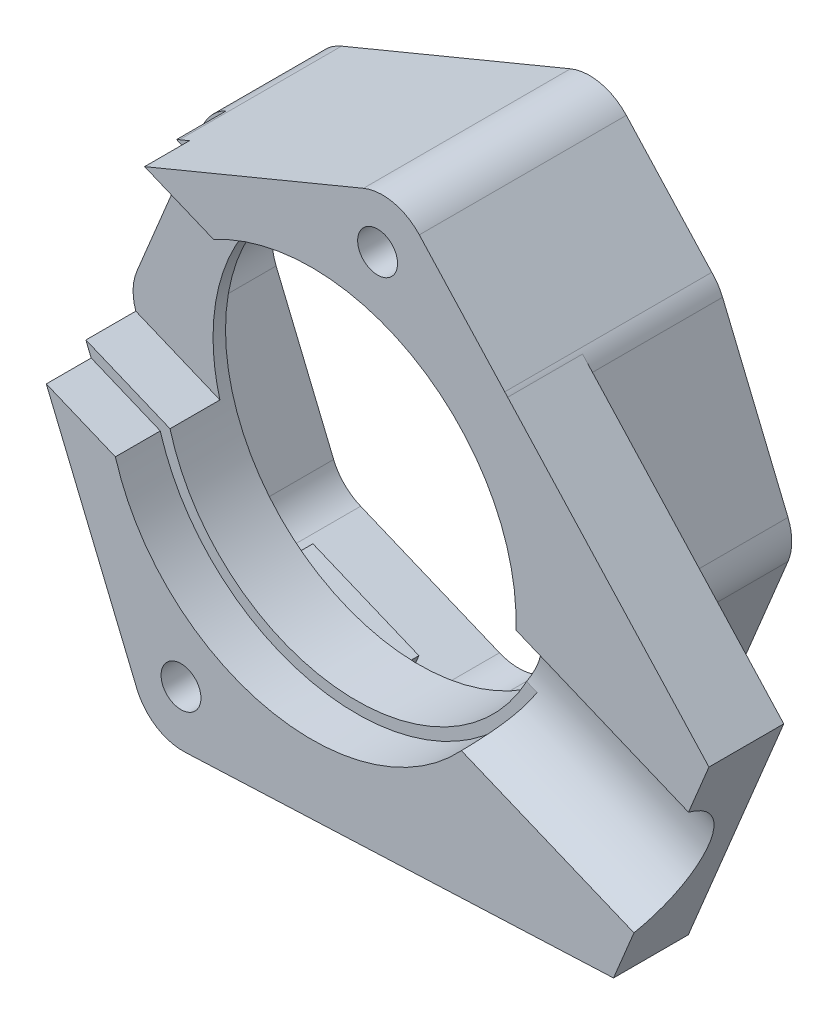
SolidWorks part; units mm, degrees
other "Markup1"
sketch "Sketch20" plane through (-10.9556, -11.1787, -0.014) normal (-0.7276, -0.6044, -0.3245) x (0.4643, -0.7821, 0.4157)
ref_plane "Front Plane" through (0, 0, 0) normal (0, 0, 1) x (1, 0, 0)
ref_plane "Top Plane" through (0, 0, 0) normal (0, 1, 0) x (1, 0, 0)
ref_plane "Right Plane" through (0, 0, 0) normal (1, 0, 0) x (0, 0, -1)
sketch "Sketch1" plane through (0, 0, 0) normal (0, 0, 1) x (1, 0, 0)
  line L0 (9.8215, 0) -> (-9.8215, 0) construction
  line L1 (0, 9.8215) -> (0, -9.8215) construction
  line L2 (-6.9448, -6.9448) -> (6.9448, 6.9448) construction
  line L3 (6.9448, -6.9448) -> (-6.9448, 6.9448) construction
  line L4 (9.8215, 0) -> (6.9448, -6.9448) construction
  line L5 (6.9448, -6.9448) -> (0, -9.8215) construction
  line L6 (0, -9.8215) -> (-6.9448, -6.9448) construction
  line L7 (-6.9448, -6.9448) -> (-9.8215, 0) construction
  line L8 (-9.8215, 0) -> (-6.9448, 6.9448) construction
  line L9 (-6.9448, 6.9448) -> (0, 9.8215) construction
  line L10 (0, 9.8215) -> (6.9448, 6.9448) construction
  line L11 (6.9448, 6.9448) -> (9.8215, 0) construction
  line L12 (8.8215, 0) -> (6.2377, -6.2377) construction
  line L13 (6.2377, -6.2377) -> (0, -8.8215) construction
  line L14 (0, -8.8215) -> (-6.2377, -6.2377) construction
  line L15 (-6.2377, -6.2377) -> (-8.8215, 0) construction
  line L16 (-8.8215, 0) -> (-6.2377, 6.2377) construction
  line L17 (-6.2377, 6.2377) -> (0, 8.8215) construction
  line L18 (0, 8.8215) -> (6.2377, 6.2377) construction
  line L19 (6.2377, 6.2377) -> (8.8215, 0) construction
  line L20 (-7.0979, 7.0979) -> (0, 10.038)
  line L21 (0, 10.038) -> (7.0979, 7.0979)
  line L22 (7.0979, 7.0979) -> (10.038, 0)
  line L23 (10.038, 0) -> (7.0979, -7.0979)
  line L24 (7.0979, -7.0979) -> (0, -10.038)
  line L25 (0, -10.038) -> (-7.0979, -7.0979)
  line L26 (-7.0979, -7.0979) -> (-10.038, 0)
  line L27 (-10.038, 0) -> (-7.0979, 7.0979)
  line L28 (-8.605, 0) -> (-6.0847, 6.0847)
  line L29 (-6.0847, 6.0847) -> (0, 8.605)
  line L30 (0, 8.605) -> (6.0847, 6.0847)
  line L31 (6.0847, 6.0847) -> (8.605, 0)
  line L32 (8.605, 0) -> (6.0847, -6.0847)
  line L33 (6.0847, -6.0847) -> (0, -8.605)
  line L34 (0, -8.605) -> (-6.0847, -6.0847)
  line L35 (-6.0847, -6.0847) -> (-8.605, 0)
  line L36 (-11.1204, 0) -> (-7.8633, 7.8633)
  line L37 (-7.8633, 7.8633) -> (0, 11.1204)
  line L38 (0, 11.1204) -> (7.8633, 7.8633)
  line L39 (7.8633, 7.8633) -> (11.1204, 0)
  line L40 (11.1204, 0) -> (7.8633, -7.8633)
  line L41 (7.8633, -7.8633) -> (0, -11.1204)
  line L42 (0, -11.1204) -> (-7.8633, -7.8633)
  line L43 (-7.8633, -7.8633) -> (-11.1204, 0)
  circle A0 centre (0, 0) radius 8.8215 construction
  circle A1 centre (0, 0) radius 9.8215 construction
  dimension "D1" = 1
  dimension "D2" = 8.15
  dimension "D3" = 45
  dimension "D4" = 45
  dimension "D5" = 0.2
  dimension "D6" = 0.2
  dimension "D7" = 1
extrude "Boss-Extrude1" add sketch "Sketch1" along normal blind 6 contours L36 L37 L38 L39 L40 L41 L42 L43 | L30 L31 L32 L33 L34 L35 L28 L29 | L21 L22 L23 L24 L25 L26 L27 L20
sketch "Sketch3" plane through (0, 0, 0) normal (0, 0, -1) x (-1, 0, 0)
  line L28 (6.0847, 6.0847) -> (0, 8.605)
  line L29 (0, 8.605) -> (-6.0847, 6.0847)
  line L30 (-6.0847, 6.0847) -> (-8.605, 0)
  line L31 (-8.605, 0) -> (-6.0847, -6.0847)
  line L32 (-6.0847, -6.0847) -> (0, -8.605)
  line L33 (0, -8.605) -> (6.0847, -6.0847)
  line L34 (6.0847, -6.0847) -> (8.605, 0)
  line L35 (8.605, 0) -> (6.0847, 6.0847)
  line L36 (6.0847, 6.0847) -> (0, 8.605)
  line L37 (0, 8.605) -> (-6.0847, 6.0847)
  line L38 (-6.0847, 6.0847) -> (-8.605, 0)
  line L39 (-8.605, 0) -> (-6.0847, -6.0847)
  line L40 (-6.0847, -6.0847) -> (0, -8.605)
  line L41 (0, -8.605) -> (6.0847, -6.0847)
  line L42 (6.0847, -6.0847) -> (8.605, 0)
  line L43 (8.605, 0) -> (6.0847, 6.0847)
  dimension "D5" = 0
extrude "Cut-Extrude1" cut sketch "Sketch3" against normal blind 4
sketch "Sketch4" plane through (0, 0, 6) normal (0, 0, 1) x (1, 0, 0)
  line L16 (-11.1204, 0) -> (-7.8633, -7.8633)
  line L17 (-7.8633, -7.8633) -> (0, -11.1204)
  line L18 (0, -11.1204) -> (7.8633, -7.8633)
  line L19 (7.8633, -7.8633) -> (11.1204, 0)
  line L20 (11.1204, 0) -> (7.8633, 7.8633)
  line L21 (7.8633, 7.8633) -> (0, 11.1204)
  line L22 (0, 11.1204) -> (-7.8633, 7.8633)
  line L23 (-7.8633, 7.8633) -> (-11.1204, 0)
  line L24 (-11.1204, 0) -> (-7.8633, -7.8633)
  line L25 (-7.8633, -7.8633) -> (0, -11.1204)
  line L26 (0, -11.1204) -> (7.8633, -7.8633)
  line L27 (7.8633, -7.8633) -> (11.1204, 0)
  line L28 (11.1204, 0) -> (7.8633, 7.8633)
  line L29 (7.8633, 7.8633) -> (0, 11.1204)
  line L30 (0, 11.1204) -> (-7.8633, 7.8633)
  line L31 (-7.8633, 7.8633) -> (-11.1204, 0)
  dimension "D1" = 0
extrude "Boss-Extrude2" add sketch "Sketch4" against normal blind 2 and the other way blind 0.5
sketch "Sketch5" plane through (0, 0, 0) normal (0, 0, -1) x (-1, 0, 0)
  line L0 (-7.6911, 5.6659) -> (-9.4514, 1.4161)
  line L1 (-7.0979, 7.0979) -> (-10.038, 0) construction
  line L2 (-9.4514, 1.4161) -> (-8.4352, 0.9951)
  line L3 (-8.4352, 0.9951) -> (-6.6748, 5.245)
  line L4 (-6.6748, 5.245) -> (-7.6911, 5.6659)
  line L5 (1.4161, -9.4514) -> (5.6659, -7.6911)
  line L6 (0, -10.038) -> (7.0979, -7.0979) construction
  line L7 (5.6659, -7.6911) -> (5.245, -6.6748)
  line L8 (5.245, -6.6748) -> (0.9951, -8.4352)
  line L9 (0.9951, -8.4352) -> (1.4161, -9.4514)
  point P10 (-8.9433, 1.2056)
  dimension "D1" = 4.6
  dimension "D2" = 4.6
  dimension "D3" = 1.55
  dimension "D4" = 1.55
extrude "Boss-Extrude3" add sketch "Sketch5" against normal up to next from offset 3 offset against normal yes
sketch "Sketch6" plane through (0, 0, 4) normal (0, 0, -1) x (-1, 0, 0)
  circle A0 centre (0, 0) radius 7.75
extrude "Cut-Extrude2" cut sketch "Sketch6" against normal through all
fillet "Fillet1" radius 2 16 edges at (7.0979, -7.0979, 2) (0, -10.038, 2) (-7.0979, -7.0979, 2) (-10.038, 0, 2) (-7.0979, 7.0979, 2) (7.0979, 7.0979, 2) (0, 10.038, 2) (0, 11.1204, 3.25) (7.8633, 7.8633, 3.25) (11.1204, 0, 3.25) (7.8633, -7.8633, 3.25) (0, -11.1204, 3.25) (-7.8633, -7.8633, 3.25) (-11.1204, 0, 3.25) (-7.8633, 7.8633, 3.25) (10.038, 0, 2)
sketch "Sketch7" plane through (0, 0, 6.5) normal (0, 0, 1) x (1, 0, 0)
  line L0 (-3.912, 6.9783) -> (-7.2819, 8.3741)
  line L1 (-9.5916, 7.4174) -> (-12.0272, 1.5374)
  line L2 (-11.0705, -0.7723) -> (-7.7006, -2.1682)
  line L3 (-7.2819, 8.3741) -> (-9.5916, 7.4174)
  line L4 (-11.0705, -0.7723) -> (-12.0272, 1.5374)
  arc A0 (-7.7006, -2.1682) -> (-3.912, 6.9783) centre (0, 0) ccw
  circle A2 centre (-7.5621, 5.7842) radius 2
  circle A3 centre (-9.4373, 1.2572) radius 2
  circle A4 centre (0, 0) radius 5
  dimension "D1" = 9.9
  dimension "D3" = 16
  dimension "D9" = 4
  dimension "D10" = 4
  dimension "D2" = 4.95
  dimension "D4" = 11.7
  dimension "D5" = 45
  dimension "D6" = 45
  dimension "D7" = 2.5
  dimension "D8" = 2.5
  dimension "D11" = 2.5
  dimension "D12" = 2.5
  dimension "D13" = 2.5
  dimension "D14" = 2.5
sketch "Sketch9" plane through (0, 0, 6.5) normal (0, 0, 1) x (1, 0, 0)
  line L16 (7.0979, 8.1803) -> (0.7654, 10.8033)
  line L17 (-0.7654, 10.8033) -> (-7.0979, 8.1803)
  line L18 (-8.1803, 7.0979) -> (-10.8033, 0.7654)
  line L19 (-10.8033, -0.7654) -> (-8.1803, -7.0979)
  line L20 (-7.0979, -8.1803) -> (-0.7654, -10.8033)
  line L21 (0.7654, -10.8033) -> (7.0979, -8.1803)
  line L22 (8.1803, -7.0979) -> (10.8033, -0.7654)
  line L23 (10.8033, 0.7654) -> (8.1803, 7.0979)
  line L24 (7.0979, 8.1803) -> (0.7654, 10.8033)
  line L25 (-0.7654, 10.8033) -> (-7.0979, 8.1803)
  line L26 (-8.1803, 7.0979) -> (-10.8033, 0.7654)
  line L27 (-10.8033, -0.7654) -> (-8.1803, -7.0979)
  line L28 (-7.0979, -8.1803) -> (-0.7654, -10.8033)
  line L29 (0.7654, -10.8033) -> (7.0979, -8.1803)
  line L30 (8.1803, -7.0979) -> (10.8033, -0.7654)
  line L31 (10.8033, 0.7654) -> (8.1803, 7.0979)
  line L125 (-3.8355, 7.163) -> (-7.2054, 8.5589)
  line L126 (-3.9245, 7.1999) -> (-6.6947, 8.3473)
  line L128 (-11.147, -0.9571) -> (-7.7771, -2.3529)
  line L129 (-10.6363, -1.1686) -> (-7.8661, -2.3161)
  arc A8 (-7.8661, -2.3161) -> (-3.9245, 7.1999) centre (0, 0) ccw
  arc A16 (0.7654, 10.8033) -> (-0.7654, 10.8033) centre (0, 8.9556) ccw
  arc A17 (-7.0979, 8.1803) -> (-8.1803, 7.0979) centre (-6.3326, 6.3326) ccw
  arc A18 (-10.8033, 0.7654) -> (-10.8033, -0.7654) centre (-8.9556, 0) ccw
  arc A19 (-8.1803, -7.0979) -> (-7.0979, -8.1803) centre (-6.3326, -6.3326) ccw
  arc A20 (-0.7654, -10.8033) -> (0.7654, -10.8033) centre (0, -8.9556) ccw
  arc A21 (7.0979, -8.1803) -> (8.1803, -7.0979) centre (6.3326, -6.3326) ccw
  arc A22 (10.8033, -0.7654) -> (10.8033, 0.7654) centre (8.9556, 0) ccw
  arc A23 (8.1803, 7.0979) -> (7.0979, 8.1803) centre (6.3326, 6.3326) ccw
  arc A24 (0.7654, 10.8033) -> (-0.7654, 10.8033) centre (0, 8.9556) ccw
  arc A25 (-7.0979, 8.1803) -> (-8.1803, 7.0979) centre (-6.3326, 6.3326) ccw
  arc A26 (-10.8033, 0.7654) -> (-10.8033, -0.7654) centre (-8.9556, 0) ccw
  arc A27 (-8.1803, -7.0979) -> (-7.0979, -8.1803) centre (-6.3326, -6.3326) ccw
  arc A28 (-0.7654, -10.8033) -> (0.7654, -10.8033) centre (0, -8.9556) ccw
  arc A29 (7.0979, -8.1803) -> (8.1803, -7.0979) centre (6.3326, -6.3326) ccw
  arc A30 (10.8033, -0.7654) -> (10.8033, 0.7654) centre (8.9556, 0) ccw
  arc A31 (8.1803, 7.0979) -> (7.0979, 8.1803) centre (6.3326, 6.3326) ccw
  line M21 (7.0979, 8.1803) -> (0.7654, 10.8033)
  arc M22 (0.7654, 10.8033) -> (-0.7654, 10.8033) centre (0, 8.9556) ccw
  line M23 (-0.7654, 10.8033) -> (-7.0979, 8.1803)
  arc M28 (-8.1803, -7.0979) -> (-7.0979, -8.1803) centre (-6.3326, -6.3326) ccw
  line M29 (-7.0979, -8.1803) -> (-0.7654, -10.8033)
  arc M30 (-0.7654, -10.8033) -> (0.7654, -10.8033) centre (0, -8.9556) ccw
  line M31 (0.7654, -10.8033) -> (7.0979, -8.1803)
  arc M32 (7.0979, -8.1803) -> (8.1803, -7.0979) centre (6.3326, -6.3326) ccw
  line M33 (8.1803, -7.0979) -> (10.8033, -0.7654)
  arc M34 (10.8033, -0.7654) -> (10.8033, 0.7654) centre (8.9556, 0) ccw
  line M35 (10.8033, 0.7654) -> (8.1803, 7.0979)
  arc M36 (8.1803, 7.0979) -> (7.0979, 8.1803) centre (6.3326, 6.3326) ccw
  dimension "D2" = 0.2
  dimension "D1" = 0
  dimension "D3" = 0.2
extrude "Boss-Extrude4" add sketch "Sketch9" along normal blind 1.8 contours A8 L129 L27 L126 M28 M29 M30 M31 M32 M33 M34 M35 M36 M21 M22 M23
sketch "Sketch10" plane through (0, 0, 6.5) normal (0, 0, 1) x (1, 0, 0)
  line L0 (-8.8488, 8.8067) -> (-3.1519, 6.4469)
  line L2 (-3.1519, 6.4469) -> (-6.7874, -2.3299)
  line L3 (-6.7874, -2.3299) -> (-12.4843, 0.0298)
  line L4 (-12.4843, 0.0298) -> (-8.8488, 8.8067)
  line L8 (-3.912, 6.9783) -> (-7.2819, 8.3741) construction
  line L9 (-11.0705, -0.7723) -> (-7.7006, -2.1682) construction
  dimension "D1" = 0.2
  dimension "D2" = 0.2
extrude "Cut-Extrude3" cut sketch "Sketch10" against normal blind 2 contours L4 L0 L2 L3
sketch "Sketch12" plane through (0, 0, 8.3) normal (0, 0, 1) x (1, 0, 0)
  line L3 (0, -10.9556) -> (12.1073, -10.427)
  line L4 (12.1073, -10.427) -> (15.9341, -1.1882)
  line L5 (15.9341, -1.1882) -> (7.7468, 7.7468)
  line L19 (0, -10.9556) -> (0.4588, -9.8479)
  line L20 (7.288, 6.6391) -> (7.7468, 7.7468)
  line L22 (9.8795, 0.3827) -> (7.2564, 6.7152)
  line L23 (7.2564, -6.7152) -> (9.8795, -0.3827)
  line L24 (0.3827, -9.8795) -> (6.7152, -7.2564)
  line L25 (9.8795, 0.3827) -> (7.288, 6.6391)
  line L26 (7.2564, -6.7152) -> (9.8795, -0.3827)
  line L27 (0.4588, -9.8479) -> (6.7152, -7.2564)
  arc A0 (-0.7654, -10.8033) -> (0.7654, -10.8033) centre (0, -8.9556) ccw construction
  arc A1 (8.1803, 7.0979) -> (7.0979, 8.1803) centre (6.3326, 6.3326) ccw construction
  arc A24 (7.2564, 6.7152) -> (6.7152, 7.2564) centre (6.3326, 6.3326) ccw
  arc A25 (9.8795, -0.3827) -> (9.8795, 0.3827) centre (8.9556, 0) ccw
  arc A26 (6.7152, -7.2564) -> (7.2564, -6.7152) centre (6.3326, -6.3326) ccw
  arc A27 (-0.3827, -9.8795) -> (0.3827, -9.8795) centre (0, -8.9556) ccw
  arc A29 (9.8795, -0.3827) -> (9.8795, 0.3827) centre (8.9556, 0) ccw
  arc A30 (6.7152, -7.2564) -> (7.2564, -6.7152) centre (6.3326, -6.3326) ccw
  dimension "D2" = 10
  dimension "D3" = 115
  dimension "D4" = 115
  dimension "D1" = 1
extrude "Boss-Extrude5" add sketch "Sketch12" against normal blind 3
sketch "Sketch11" plane through (14.0207, -5.8076, 0) normal (0.9239, -0.3827, 0) x (0, 0, -1)
  line L0 (-8.3, -3.4272) -> (-8.3, 3.4272) construction
  circle A0 centre (-9.5, 0) radius 3.1
  dimension "D1" = 1.2
extrude "Cut-Extrude4" cut sketch "Sketch11" against normal up to surface (8.0729 mm away) contours A0
sketch "Sketch13" plane through (0, 0, 8.3) normal (0, 0, 1) x (1, 0, 0)
  line L0 (-8.1803, -7.0979) -> (-7.0014, -9.9441)
  line L2 (0.1743, -10.948) -> (-5.0664, -11.1768)
  line L4 (-8.1803, -7.0979) -> (0.1743, -10.948)
  line L5 (7.8646, 7.6181) -> (4.3207, 11.4857)
  line L7 (-0.7654, 10.8033) -> (2.0808, 11.9823)
  line L9 (-0.7654, 10.8033) -> (7.8646, 7.6181)
  arc A0 (-7.0014, -9.9441) -> (-5.0664, -11.1768) centre (-5.1536, -9.1787) ccw
  arc A1 (4.3207, 11.4857) -> (2.0808, 11.9823) centre (2.8461, 10.1345) ccw
  dimension "D1" = 2
extrude "Boss-Extrude6" add sketch "Sketch13" against normal up to surface (8.3 mm away) up to face at (0, 0, 0)
sketch "Sketch14" plane through (0, 0, 8.3) normal (0, 0, 1) x (1, 0, 0)
  line L0 (-0.0089, -0.0215) -> (7.7271, 18.6549) construction
  line L1 (-5.2351, -8.9802) -> (-1.2934, 0.5358) construction
  line L2 (0.0034, -0.0014) -> (-15.1897, 6.2918) construction
  line L4 (-1.2934, 0.5358) -> (2.6482, 10.0517) construction
  circle A0 centre (2.6482, 10.0517) radius 1
  circle A1 centre (-5.2351, -8.9802) radius 1
  dimension "D1" = 90
  dimension "D3" = 2
  dimension "D4" = 2
  dimension "D2" = 1.4
  dimension "D5" = 1.4
  dimension "D7" = 10.3
  dimension "D8" = 10.3
  dimension "D9" = 0
hole_wizard "Tap Drill for M2x0.4 Tap1" positions "Sketch18" profile "Sketch19" hole size "M2x0.4" standard "ANSI Metric"
sketch "Sketch18" plane through (0, 0, 8.3) normal (0, 0, 1) x (1, 0, 0)
  point P0 (-5.2351, -8.9802)
  point P3 (2.6482, 10.0517)
sketch "Sketch19" plane through (-5.2351, -8.9802, 8.3) normal (1, 0, 0) x (0, -1, 0)
  line L0 (0, 0) -> (0, 5.4807)
  line L1 (0, 5.4807) -> (0.8, 5)
  line L2 (0.8, 5) -> (0.8, 0)
  line L5 (0.8, 0) -> (0, 0)
  line L10 (0, 5.4807) -> (-0.8, 5) construction
  line L11 (0, -6.35) -> (0, 107.95) construction
  dimension "Hole Dia." = 1.6
  dimension "Hole Depth" = 5
  dimension "Drill Angle" = 118
fillet "Fillet2" radius 0.5 4 edges at (-5.6659, -7.6911, 3.5) (-1.4161, -9.4514, 3.5) (9.4514, 1.4161, 3.5) (7.6911, 5.6659, 3.5)
